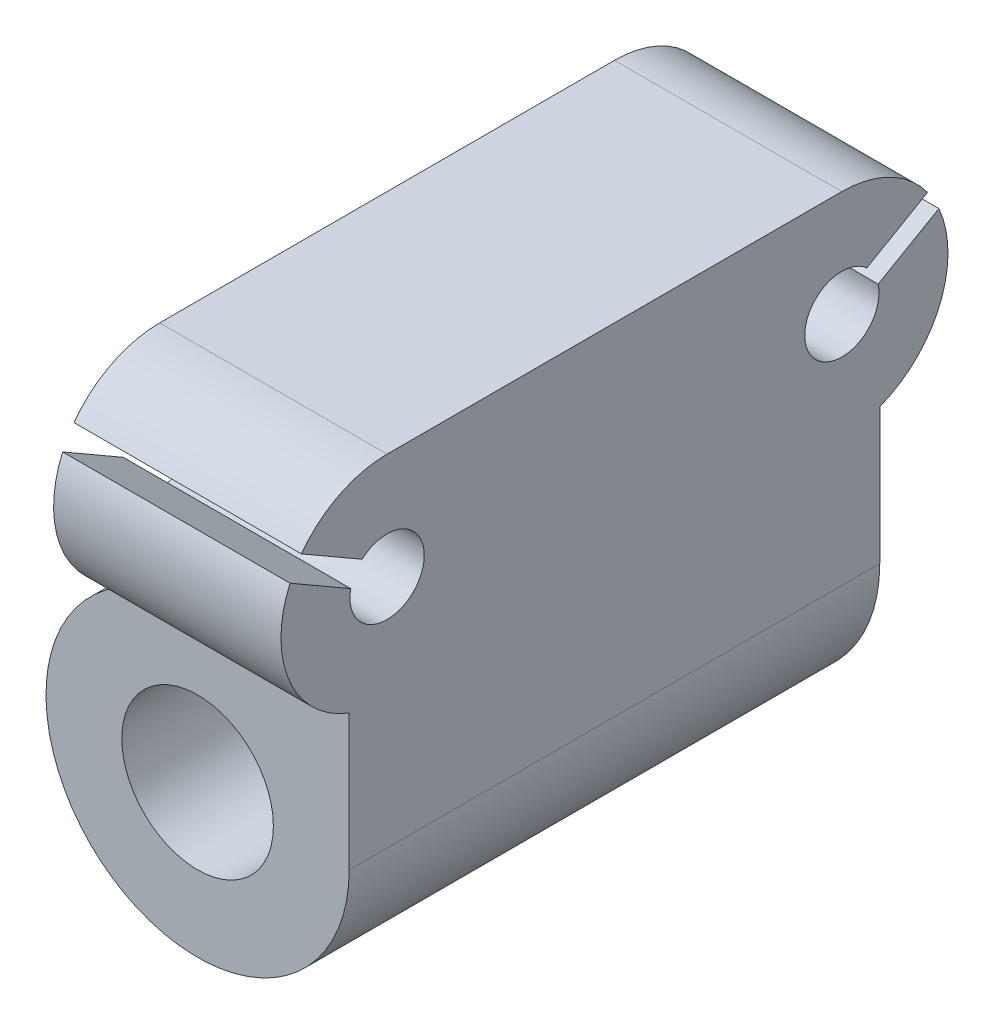
SolidWorks part; units mm, degrees
ref_plane "Front Plane" through (0, 0, 0) normal (0, 0, 1) x (1, 0, 0)
ref_plane "Top Plane" through (0, 0, 0) normal (0, 1, 0) x (1, 0, 0)
ref_plane "Right Plane" through (0, 0, 0) normal (1, 0, 0) x (0, 0, -1)
sketch "Sketch1" plane through (0, 0, 0) normal (0, 0, 1) x (1, 0, 0)
  line L1 (0, 12) -> (10, 12)
  line L2 (10, 12) -> (10, 0)
  line L3 (0, 10) -> (0, 12)
  circle A0 centre (0, 0) radius 5
  arc A1 (0, 10) -> (10, 0) centre (0, 0) ccw
  arc A2 (-10, 0) -> (10, 0) centre (0, 0) cw construction
  dimension "D1" = 10
  dimension "D2" = 20
  dimension "D3" = 12
extrude "Boss-Extrude1" add sketch "Sketch1" along normal blind 15
sketch "Sketch3" plane through (0, 0, 15) normal (0, 0, 1) x (1, 0, 0)
  line L0 (10, 0) -> (10, 12)
  line L1 (10, 12) -> (0, 12)
  line L3 (0, 12) -> (0, 10) construction
  line L4 (0, 12) -> (0, 10)
  line L5 (10, 0) -> (10, 12) construction
  line L6 (10, 12) -> (0, 12) construction
  circle A0 centre (0, 0) radius 3.5
  arc A1 (-10, 0) -> (10, 0) centre (0, 0) ccw
  arc A2 (-10, 0) -> (0, 10) centre (0, 0) cw
  circle A3 centre (0, 0) radius 5 construction
  dimension "D1" = 7
  dimension "D2" = 20
extrude "Boss-Extrude2" add sketch "Sketch3" along normal blind 5
sketch "Sketch4" plane through (0, 0, 20) normal (0, 0, 1) x (1, 0, 0)
  line L0 (10, 0) -> (10, 12) construction
  line L1 (0, 12) -> (10, 12)
  line L2 (10, 12) -> (10, 0)
  line L3 (0, 12) -> (0, 10)
  circle A0 centre (0, 0) radius 5
  arc A1 (0, 10) -> (10, 0) centre (0, 0) ccw
  arc A2 (0, 10) -> (10, 0) centre (0, 0) cw construction
  dimension "D1" = 10
  dimension "D3" = 12
extrude "Boss-Extrude3" add sketch "Sketch4" along normal blind 15
ref_plane "Plane1" through (0, 0, 0) normal (-1, 0, 0) x (0, 0, 1)
sketch "Sketch6" plane through (0, 0, 0) normal (-1, 0, 0) x (0, 0, 1)
  line L0 (2.5, 15.5) -> (32.5, 15.5) construction
  line L1 (9.5, 22.5) -> (2.5, 22.5)
  line L2 (9.5, 22.5) -> (25.5, 22.5)
  line L3 (25.5, 22.5) -> (32.5, 22.5)
  line L4 (9.5, 15.5) -> (25.5, 15.5) construction
  line L5 (9.5, 22.5) -> (9.5, 15.5) construction
  line L6 (25.5, 15.5) -> (25.5, 22.5) construction
  line L7 (2.5, 15.5) -> (2.5, 8.5) construction
  line L8 (2.5, 8.5) -> (32.5, 8.5)
  line L9 (32.5, 8.5) -> (32.5, 15.5) construction
  line L10 (35, 12) -> (0, 12) construction
  line L13 (35, 12) -> (0, 12) construction
  arc A0 (2.5, 22.5) -> (2.5, 8.5) centre (2.5, 15.5) ccw
  arc A1 (32.5, 8.5) -> (32.5, 22.5) centre (32.5, 15.5) ccw
  arc A2 (2.5, 22.5) -> (9.5, 15.5) centre (2.5, 15.5) cw construction
  arc A3 (32.5, 22.5) -> (25.5, 15.5) centre (32.5, 15.5) ccw construction
  point P8 (2.5, 12)
  point P11 (32.5, 12)
  point P14 (17.5, 15.5)
  point P15 (17.5, 12)
  dimension "D3" = 7
  dimension "D1" = 30
extrude "Boss-Extrude4" add sketch "Sketch6" along normal blind 5 and the other way blind 10
sketch "Sketch7" plane through (-5, 0, 0) normal (-1, 0, 0) x (0, 0, 1)
  circle A0 centre (2.5, 15.5) radius 2.45
  circle A1 centre (32.5, 15.5) radius 2.45
  dimension "D1" = 4.9
extrude "Cut-Extrude1" cut sketch "Sketch7" against normal through all
sketch "Sketch8" plane through (10, 0, 0) normal (1, 0, 0) x (0, 0, -1)
  line L0 (-32.125, 16.1495) -> (-32.875, 14.8505)
  line L1 (-32.125, 16.1495) -> (-38.1872, 19.6495)
  line L2 (-32.875, 14.8505) -> (-38.9372, 18.3505)
  line L3 (-38.1872, 19.6495) -> (-38.9372, 18.3505)
  line L4 (-2.875, 16.1495) -> (-2.125, 14.8505)
  line L5 (-2.875, 16.1495) -> (3.1872, 19.6495)
  line L6 (-2.125, 14.8505) -> (3.9372, 18.3505)
  line L7 (3.1872, 19.6495) -> (3.9372, 18.3505)
  line L8 (-35, 0) -> (-35, 8.9617) construction
  line L9 (0, 0) -> (0, 8.9617) construction
  arc A0 (-32.5, 22.5) -> (-35, 8.9617) centre (-32.5, 15.5) ccw construction
  arc A1 (0, 8.9617) -> (-2.5, 22.5) centre (-2.5, 15.5) ccw construction
  point P0 (-32.5, 15.5)
  point P3 (-2.5, 15.5)
  dimension "D1" = 120
  dimension "D2" = 120
  dimension "D3" = 1.5
  dimension "D4" = 1.5
extrude "Cut-Extrude2" cut sketch "Sketch8" against normal through all
